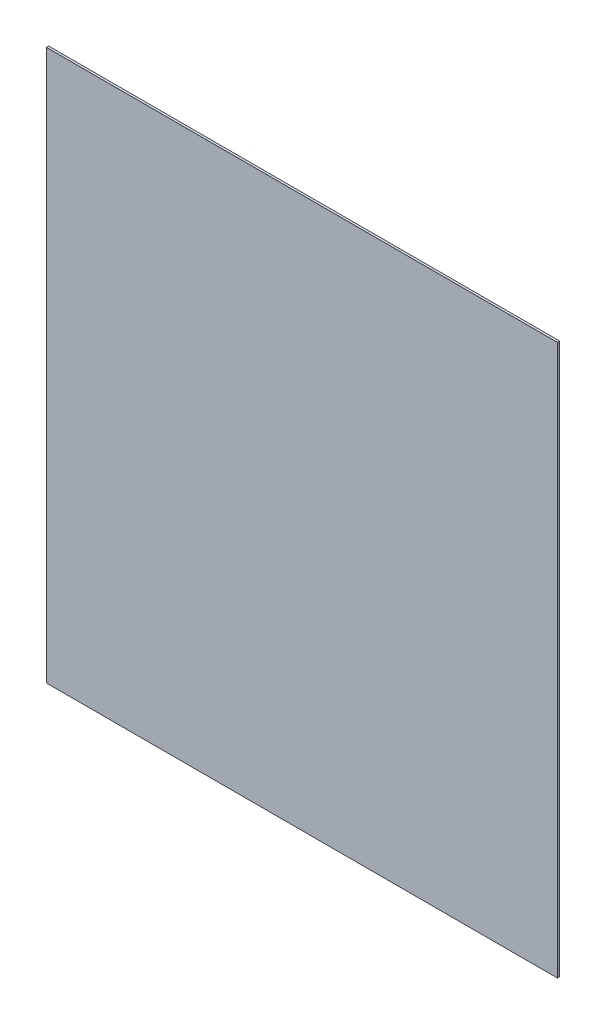
SolidWorks part; units mm, degrees
ref_plane "Front" through (0, 0, 0) normal (0, 0, 1) x (1, 0, 0)
ref_plane "Top" through (0, 0, 0) normal (0, 1, 0) x (1, 0, 0)
ref_plane "Right" through (0, 0, 0) normal (1, 0, 0) x (0, 0, -1)
sketch "Sketch1" plane through (0, 0, 0) normal (0, 0, 1) x (1, 0, 0)
  line L1 (-279.4, -300.99) -> (279.4, -300.99)
  line L2 (-279.4, -300.99) -> (-279.4, 300.99)
  line L3 (-279.4, 300.99) -> (279.4, 300.99)
  line L4 (279.4, -300.99) -> (279.4, 300.99)
  line L5 (-279.4, -300.99) -> (279.4, 300.99) construction
  line L6 (-279.4, 300.99) -> (279.4, -300.99) construction
  point P0 (0, 0)
  dimension "D1" = 558.8
  dimension "D2" = 601.98
extrude "Boss-Extrude1" add sketch "Sketch1" along normal blind 2.54
